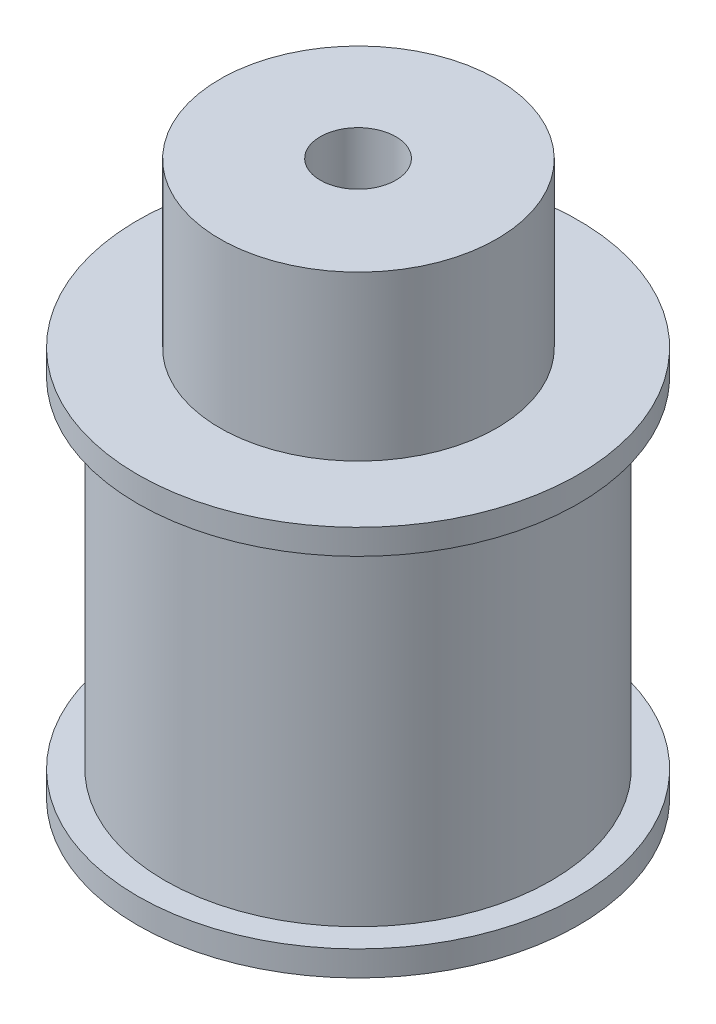
SolidWorks part; units mm, degrees
ref_plane "前视基准面" through (0, 0, 0) normal (0, 0, 1) x (1, 0, 0)
ref_plane "上视基准面" through (0, 0, 0) normal (0, 1, 0) x (1, 0, 0)
ref_plane "右视基准面" through (0, 0, 0) normal (1, 0, 0) x (0, 0, -1)
other "Configuration Table"
sketch "草图1" plane through (0, 0, 0) normal (0, 1, 0) x (1, 0, 0)
  circle A0 centre (0, 0) radius 15.345
  dimension "D1" = 30.69
extrude "凸台-拉伸1" add sketch "草图1" along normal mid plane 27
sketch "草图2" plane through (0, 13.5, 0) normal (0, 1, 0) x (1, 0, 0)
  circle A0 centre (0, 0) radius 17.5
  dimension "D1" = 35
extrude "凸台-拉伸2" add sketch "草图2" along normal blind 2
mirror "镜向1" about plane through (0, 0, 0) normal (0, 1, 0) of "凸台-拉伸2"
sketch "草图4" plane through (0, 15.5, 0) normal (0, 1, 0) x (1, 0, 0)
  circle A0 centre (0.058, -0.0292) radius 11
  dimension "D1" = 22
extrude "凸台-拉伸3" add sketch "草图4" along normal blind 13
sketch "草图3" plane through (0, -15.5, 0) normal (0, 1, 0) x (1, 0, 0)
  circle A0 centre (0, 0) radius 3
  dimension "D1" = 6
extrude "切除-拉伸1" cut sketch "草图3" along normal through all
